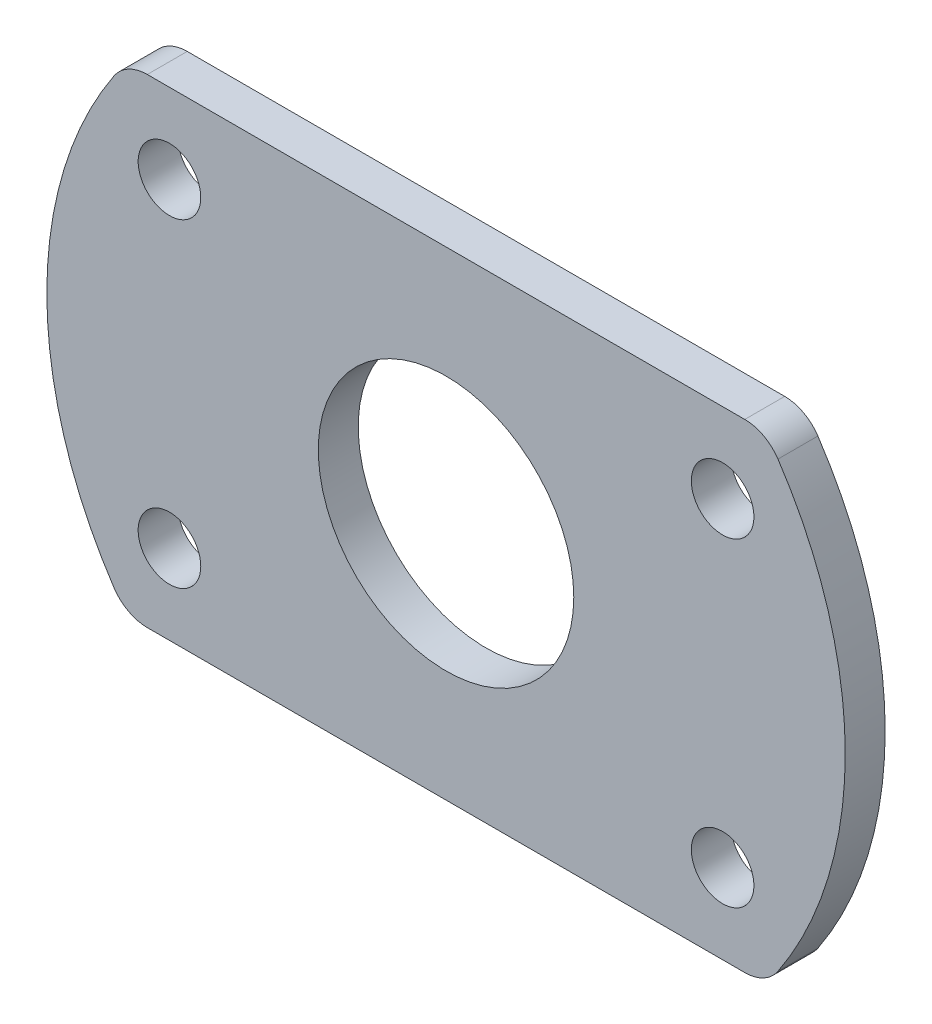
SolidWorks part; units mm, degrees
material "6061-T6 (SS)"
ref_plane "Front Plane" through (0, 0, 0) normal (0, 0, 1) x (1, 0, 0)
ref_plane "Top Plane" through (0, 0, 0) normal (0, 1, 0) x (1, 0, 0)
ref_plane "Right Plane" through (0, 0, 0) normal (1, 0, 0) x (0, 0, -1)
sketch "Sketch1" plane through (0, 0, 0) normal (0, 0, 1) x (1, 0, 0)
  line L0 (-25.4, 19.05) -> (0, 19.05)
  line L1 (0, 19.05) -> (25.4, 19.05)
  line L2 (-31.75, 0) -> (31.75, 0) construction
  line L3 (0, -19.05) -> (25.4, -19.05)
  line L4 (-25.4, -19.05) -> (0, -19.05)
  arc A0 (25.4, -19.05) -> (25.4, 19.05) centre (0, 0) ccw
  circle A1 centre (0, 0) radius 25.4 construction
  circle A2 centre (0, 25.4) radius 2.4892 construction
  circle A3 centre (21.997, 12.7) radius 2.4892
  circle A4 centre (21.997, -12.7) radius 2.4892
  circle A5 centre (0, -25.4) radius 2.4892 construction
  circle A6 centre (-21.997, -12.7) radius 2.4892
  circle A7 centre (-21.997, 12.7) radius 2.4892
  circle A8 centre (0, 0) radius 10.16
  arc A9 (-25.4, -19.05) -> (25.4, -19.05) centre (0, 0) ccw construction
  arc A10 (25.4, 19.05) -> (-25.4, 19.05) centre (0, 0) ccw construction
  arc A11 (-25.4, 19.05) -> (-25.4, -19.05) centre (0, 0) ccw
  point P18 (0, 0)
  dimension "D1" = 50.8
  dimension "D2" = 4.9784
  dimension "D4" = 6.35
  dimension "D5" = 20.32
  dimension "D6" = 25.4
  dimension "D7" = 19.05
  dimension "D3" = 6
extrude "Boss-Extrude1" add sketch "Sketch1" along normal mid plane 3.175
fillet "Fillet1" radius 3.175 4 edges at (-25.4, 19.05, 0) (25.4, 19.05, 0) (25.4, -19.05, 0) (-25.4, -19.05, 0)
